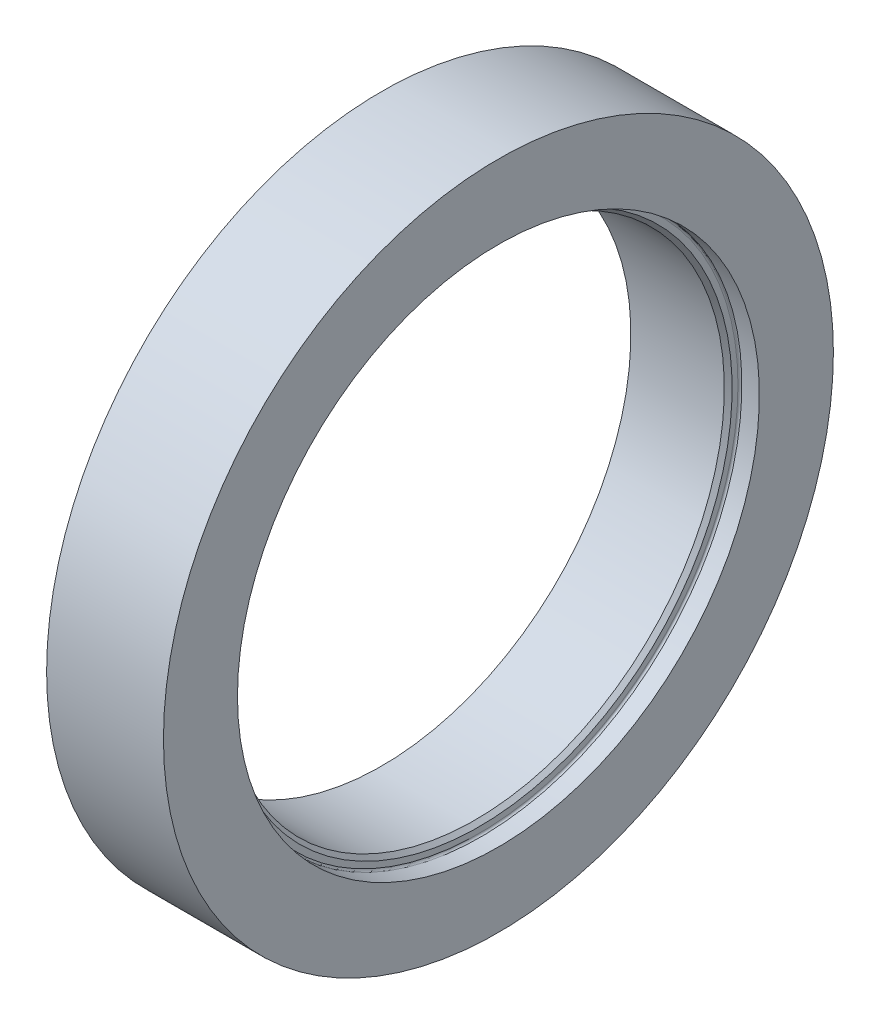
SolidWorks part; units mm, degrees
material "Алюминиевая бронза"
ref_plane "Спереди" through (0, 0, 0) normal (0, 0, 1) x (1, 0, 0)
ref_plane "Сверху" through (0, 0, 0) normal (0, 1, 0) x (1, 0, 0)
ref_plane "Справа" through (0, 0, 0) normal (1, 0, 0) x (0, 0, -1)
sketch "Эскиз1" plane through (0, 0, 0) normal (0, 0, 1) x (1, 0, 0)
  line L0 (0, 0) -> (30, 0) construction
  line L1 (0, 64) -> (0, 86)
  line L2 (0, 86) -> (30, 86)
  line L3 (30, 86) -> (30, 67)
  line L4 (30, 67) -> (25.5, 67)
  line L5 (25, 66.5) -> (25, 65)
  line L6 (24, 64) -> (0, 64)
  line L7 (25, 65) -> (24, 64)
  arc A0 (25.5, 67) -> (25, 66.5) centre (25.5, 66.5) ccw
  point P9 (25, 64)
  point P11 (25, 67)
  dimension "D6" = 0.5
  dimension "D1" = 30
  dimension "D2" = 5
  dimension "D3" = 128
  dimension "D4" = 172
  dimension "D5" = 134
  dimension "D7" = 1
  dimension "D8" = 45
revolve "Повернуть1" add sketch "Эскиз1" angle 360 about L0
